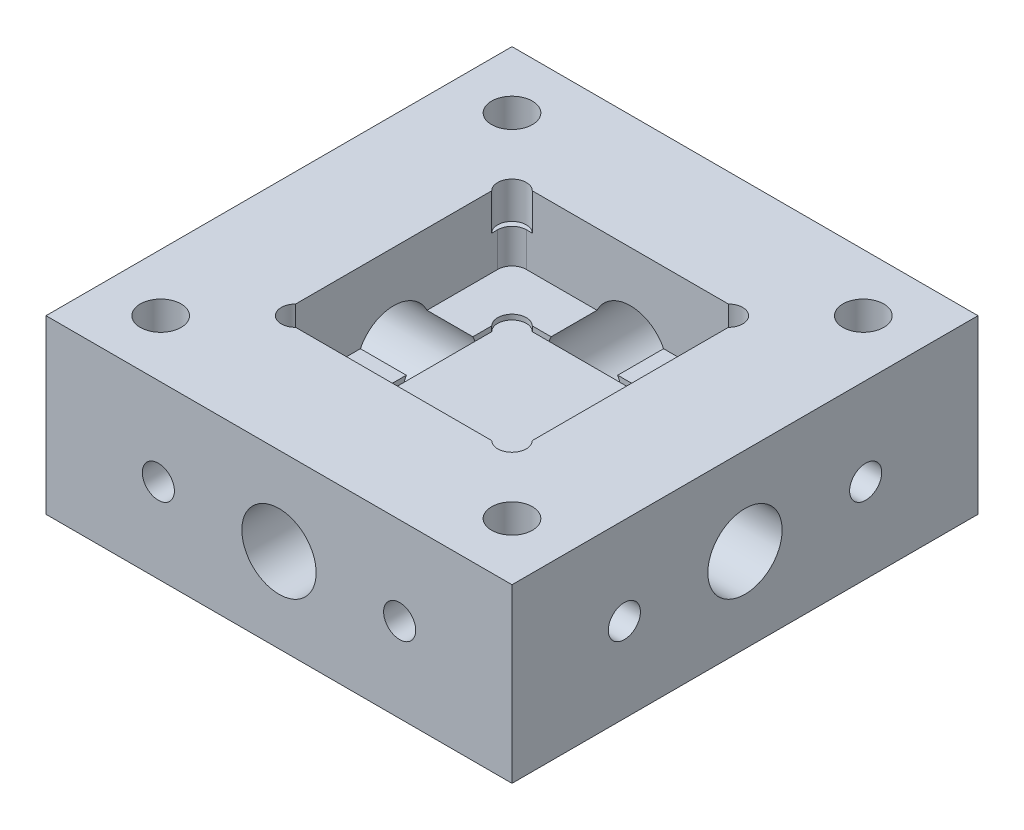
SolidWorks part; units mm, degrees
ref_plane "Front Plane" through (0, 0, 0) normal (0, 0, 1) x (1, 0, 0)
ref_plane "Top Plane" through (0, 0, 0) normal (0, 1, 0) x (1, 0, 0)
ref_plane "Right Plane" through (0, 0, 0) normal (1, 0, 0) x (0, 0, -1)
sketch "Sketch1" plane through (0, 0, 0) normal (0, 1, 0) x (1, 0, 0)
  line L1 (-12.9, -12.9) -> (12.9, -12.9)
  line L2 (-12.9, -12.9) -> (-12.9, 12.9)
  line L3 (-12.9, 12.9) -> (12.9, 12.9)
  line L4 (12.9, -12.9) -> (12.9, 12.9)
  line L5 (-12.9, -12.9) -> (12.9, 12.9) construction
  line L6 (-12.9, 12.9) -> (12.9, -12.9) construction
  point P0 (0, 0)
  dimension "D1" = 25.8
  dimension "D2" = 25.8
extrude "Boss-Extrude1" add sketch "Sketch1" along normal blind 9.525
sketch "Sketch3" plane through (-12.9, 0, 0) normal (-1, 0, 0) x (0, 0, 1)
  line L0 (-12.9, 9.525) -> (12.9, 9.525) construction
  circle A0 centre (0, 4.6736) radius 2.0574
  dimension "D1" = 4.1148
  dimension "D2" = 4.8514
extrude "Cut-Extrude3" cut sketch "Sketch3" against normal blind 8.89
mirror "Mirror1" about plane through (0, 0, 0) normal (1, 0, 0) of "Cut-Extrude3"
sketch "Sketch7" plane through (0, 0, -12.9) normal (0, 0, -1) x (-1, 0, 0)
  line L0 (-12.9, 9.525) -> (12.9, 9.525) construction
  circle A0 centre (0, 4.6736) radius 2.0574
  dimension "D1" = 4.1148
  dimension "D2" = 4.8514
extrude "Cut-Extrude5" cut sketch "Sketch7" against normal blind 8.89
mirror "Mirror2" about plane through (0, 0, 0) normal (0, 0, 1) of "Cut-Extrude5"
sketch "Sketch8" plane through (12.9, 0, 0) normal (1, 0, 0) x (0, 0, -1)
  point P3 (6.6802, 5.2324)
sketch "Sketch12" plane through (0, 9.525, 0) normal (0, 1, 0) x (1, 0, 0)
  line L10 (9.725, -9.725) -> (9.725, 9.725)
  line L11 (9.725, 9.725) -> (-9.725, 9.725)
  line L12 (-9.725, 9.725) -> (-9.725, -9.725)
  line L14 (-9.725, -9.725) -> (9.725, -9.725)
  line L15 (9.725, -9.725) -> (9.725, 9.725)
  line L16 (9.725, 9.725) -> (-9.725, 9.725)
  line L17 (-9.725, 9.725) -> (-9.725, -9.725)
  line L18 (-9.725, -9.725) -> (9.725, -9.725)
  dimension "D1" = 3.175
sketch "Sketch14" plane through (0, 9.525, 0) normal (0, 1, 0) x (1, 0, 0)
  line L1 (-5.7562, -6.55) -> (5.7562, -6.55)
  line L2 (-6.55, -5.7562) -> (-6.55, 5.7562)
  line L3 (-5.7562, 6.55) -> (5.7562, 6.55)
  line L4 (6.55, -5.7562) -> (6.55, 5.7562)
  line L5 (-6.55, -6.55) -> (6.55, 6.55) construction
  line L6 (-6.55, 6.55) -> (6.55, -6.55) construction
  arc A0 (5.7562, -6.55) -> (6.55, -5.7562) centre (5.7562, -5.7562) ccw
  arc A1 (-6.55, -5.7562) -> (-5.7562, -6.55) centre (-5.7562, -5.7562) ccw
  arc A2 (6.55, 5.7562) -> (5.7562, 6.55) centre (5.7562, 5.7562) ccw
  arc A3 (-6.55, 5.7562) -> (-5.7562, 6.55) centre (-5.7562, 5.7562) cw
  point P0 (0, 0)
  dimension "D3" = 0.7937
  dimension "D1" = 13.1
  dimension "D2" = 13.1
extrude "Cut-Extrude10" cut sketch "Sketch14" against normal blind 3.9376
sketch "Sketch15" plane through (0, 5.5874, 0) normal (0, 1, 0) x (1, 0, 0)
  line L5 (-4.01, -4.01) -> (4.01, 4.01) construction
  line L6 (-4.01, 4.01) -> (4.01, -4.01) construction
  line L7 (-2.8875, 4.01) -> (2.8875, 4.01)
  line L8 (-4.01, 2.8875) -> (-4.01, -2.8875)
  line L9 (-2.8875, -4.01) -> (2.8875, -4.01)
  line L10 (4.01, 2.8875) -> (4.01, -2.8875)
  arc A4 (-2.8875, 4.01) -> (-4.01, 2.8875) centre (-3.4487, 3.4487) ccw
  arc A5 (4.01, 2.8875) -> (2.8875, 4.01) centre (3.4487, 3.4487) ccw
  arc A6 (2.8875, -4.01) -> (4.01, -2.8875) centre (3.4487, -3.4487) ccw
  arc A7 (-4.01, -2.8875) -> (-2.8875, -4.01) centre (-3.4487, -3.4487) ccw
  point P0 (0, 0)
  point P16 (0, 0)
  point P27 (0, 0)
  dimension "D3" = 0.7937
  dimension "D1" = 8.02
  dimension "D2" = 8.02
  dimension "D4" = 4
extrude "Cut-Extrude11" cut sketch "Sketch15" against normal blind 0.28
sketch "Sketch16" plane through (0, 0, -12.9) normal (0, 0, -1) x (-1, 0, 0)
  point P3 (6.6802, 5.2324)
hole_wizard "#4-40 Tapped Hole2" positions "Sketch18" profile "Sketch19" tap size "#4-40" standard "ANSI Inch" end condition through all
sketch "Sketch18" plane through (0, 9.525, 0) normal (0, 1, 0) x (1, 0, 0)
  point P0 (9.725, -9.725)
  point P3 (-9.725, -9.725)
  point P6 (-9.725, 9.725)
  point P9 (9.725, 9.725)
sketch "Sketch19" plane through (9.725, 9.525, 9.725) normal (1, 0, 0) x (0, 0, 1)
  line L0 (0, 0) -> (0, 9.525)
  line L1 (0, 9.525) -> (1.1303, 9.525)
  line L2 (1.1303, 9.525) -> (1.1303, 0)
  line L5 (1.1303, 0) -> (0, 0)
  line L11 (0, -6.35) -> (0, 107.95) construction
  dimension "Thru Tap Drill Dia." = 2.2606
  dimension "Thru Tap Drill Depth" = 9.525
cosmetic thread "Hole Thread13" parameters "D2"=2.8448
cosmetic thread "Hole Thread14" parameters "D2"=2.8448
cosmetic thread "Hole Thread15" parameters "D2"=2.8448
cosmetic thread "Hole Thread16" parameters "D2"=2.8448
hole_wizard "#2-56 Tapped Hole1" positions "Sketch20" profile "Sketch22" tap size "#2-56" standard "ANSI Inch"
sketch "Sketch20" plane through (0, 0, -12.9) normal (0, 0, -1) x (-1, 0, 0)
  line L0 (-12.9, 9.525) -> (12.9, 9.525) construction
  point P0 (6.6802, 4.6736)
  dimension "D1" = 4.8514
cosmetic thread "Hole Thread17" parameters "D1"=4.826, "D2"=2.1844
sketch "Sketch22" plane through (-6.6802, 4.6736, -12.9) normal (1, 0, 0) x (0, 1, 0)
  line L0 (0, 0) -> (0, 5.6142)
  line L1 (0, 5.6142) -> (0.889, 5.08)
  line L2 (0.889, 5.08) -> (0.889, 0)
  line L5 (0.889, 0) -> (0, 0)
  line L10 (0, 5.6142) -> (-0.889, 5.08) construction
  line L11 (0, -6.35) -> (0, 107.95) construction
  dimension "Tap Drill Dia." = 1.778
  dimension "Tap Drill Depth" = 5.08
  dimension "Drill Angle" = 118
mirror "Mirror7" about plane through (0, 0, 0) normal (1, 0, 0) of "#2-56 Tapped Hole1"
mirror "Mirror8" about plane through (0, 0, 0) normal (0, 0, 1) of "Mirror7", "#2-56 Tapped Hole1"
hole_wizard "#2-56 Tapped Hole2" positions "Sketch23" profile "Sketch24" tap size "#2-56" standard "ANSI Inch"
sketch "Sketch23" plane through (12.9, 0, 0) normal (1, 0, 0) x (0, 0, -1)
  line L0 (-12.9, 9.525) -> (12.9, 9.525) construction
  point P0 (6.6802, 4.6736)
  dimension "D1" = 4.8514
sketch "Sketch24" plane through (12.9, 4.6736, -6.6802) normal (0, 1, 0) x (0, 0, -1)
  line L0 (0, 0) -> (0, 5.6142)
  line L1 (0, 5.6142) -> (0.889, 5.08)
  line L2 (0.889, 5.08) -> (0.889, 0)
  line L5 (0.889, 0) -> (0, 0)
  line L10 (0, 5.6142) -> (-0.889, 5.08) construction
  line L11 (0, -6.35) -> (0, 107.95) construction
  dimension "Tap Drill Dia." = 1.778
  dimension "Tap Drill Depth" = 5.08
  dimension "Drill Angle" = 118
cosmetic thread "Hole Thread18" parameters "D1"=4.826, "D2"=2.1844
mirror "Mirror9" about plane through (0, 0, 0) normal (0, 0, 1) of "#2-56 Tapped Hole2"
mirror "Mirror10" about plane through (0, 0, 0) normal (1, 0, 0) of "Mirror9", "#2-56 Tapped Hole2"
sketch "Sketch25" plane through (0, 9.525, 0) normal (0, 1, 0) x (1, 0, 0)
  line L9 (-5.4275, -6.55) -> (5.4275, -6.55)
  line L10 (-6.55, -5.4275) -> (-6.55, 5.4275)
  line L11 (-5.4275, 6.55) -> (5.4275, 6.55)
  line L12 (6.55, -5.4275) -> (6.55, 5.4275)
  line L13 (-6.55, -6.55) -> (6.55, 6.55) construction
  line L14 (-6.55, 6.55) -> (6.55, -6.55) construction
  arc A0 (-6.55, 6.55) -> (-5.4275, 6.55) centre (-5.9887, 5.9887) cw
  arc A1 (-6.55, 6.55) -> (-6.55, 5.4275) centre (-5.9887, 5.9887) ccw
  arc A2 (6.55, 6.55) -> (6.55, 5.4275) centre (5.9887, 5.9887) cw
  arc A3 (6.55, 6.55) -> (5.4275, 6.55) centre (5.9887, 5.9887) ccw
  arc A4 (6.55, -6.55) -> (5.4275, -6.55) centre (5.9887, -5.9887) cw
  arc A5 (6.55, -6.55) -> (6.55, -5.4275) centre (5.9887, -5.9887) ccw
  arc A6 (-6.55, -6.55) -> (-6.55, -5.4275) centre (-5.9887, -5.9887) cw
  arc A7 (-6.55, -6.55) -> (-5.4275, -6.55) centre (-5.9887, -5.9887) ccw
  point P0 (0, 0)
  point P16 (0, 0)
  point P18 (0, 0)
  point P26 (0, 0)
  dimension "D1" = 0.7937
  dimension "D4" = 13.1
  dimension "D5" = 13.1
extrude "Cut-Extrude12" cut sketch "Sketch25" against normal blind 2.032
sketch "Sketch26" plane through (0, 9.525, 0) normal (0, 1, 0) x (1, 0, 0)
  point P7 (-5.9887, 5.9887)
  point P8 (5.9887, 5.9887)
  point P9 (5.9887, -5.9887)
  point P10 (-5.9887, -5.9887)
sketch "Sketch27" plane through (0, 5.3074, 0) normal (0, 1, 0) x (1, 0, 0)
  point P7 (-3.4487, 3.4487)
  point P8 (3.4487, 3.4487)
  point P9 (3.4487, -3.4487)
  point P10 (-3.4487, -3.4487)
